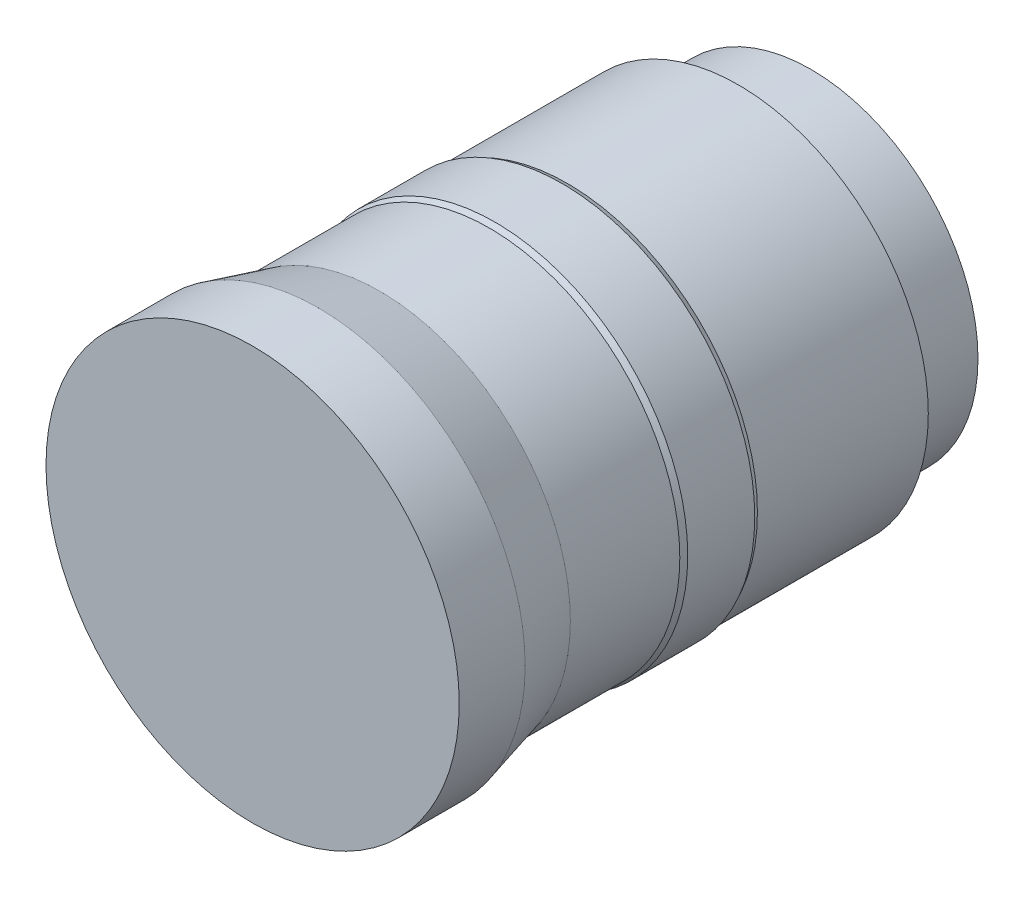
SolidWorks part; units mm, degrees
ref_plane "前视基准面" through (0, 0, 0) normal (0, 0, 1) x (1, 0, 0)
ref_plane "上视基准面" through (0, 0, 0) normal (0, 1, 0) x (1, 0, 0)
ref_plane "右视基准面" through (0, 0, 0) normal (1, 0, 0) x (0, 0, -1)
sketch "草图1" plane through (0, 0, 0) normal (1, 0, 0) x (0, 0, -1)
  line L0 (-16.4895, 0) -> (18.7339, 0) construction
  line L1 (0, 0) -> (0, 14.95)
  line L2 (0, 14.95) -> (-6.5, 14.95)
  line L3 (-6.5, 14.95) -> (-6.5, 17)
  line L4 (-6.5, 17) -> (-21.8, 17)
  line L5 (-21.8, 17) -> (-22.2888, 17.25)
  line L6 (-22.2888, 17.25) -> (-28.2888, 17.25)
  line L7 (-28.2888, 17.25) -> (-28.8, 17.05)
  line L8 (-28.8, 17.05) -> (-38.6, 17.05)
  line L9 (-38.6, 17.05) -> (-44.1, 18.5)
  line L10 (-44.1, 18.5) -> (-50, 18.5)
  line L11 (-50, 18.5) -> (-50, 0)
  line L12 (-50, 0) -> (0, 0)
  line L13 (-28.8, 17.05) -> (-21.8, 17) construction
  line L14 (-25.3, 17.025) -> (-25.3, 17.25) construction
  dimension "D1" = 34
  dimension "D2" = 50
  dimension "D3" = 37
  dimension "D4" = 34.1
  dimension "D5" = 29.9
  dimension "D6" = 6.5
  dimension "D7" = 15.3
  dimension "D8" = 6
  dimension "D9" = 0.2
  dimension "D10" = 11.4
  dimension "D11" = 5.9
  dimension "D12" = 7
revolve "旋转1" add sketch "草图1" angle 360 about L12
